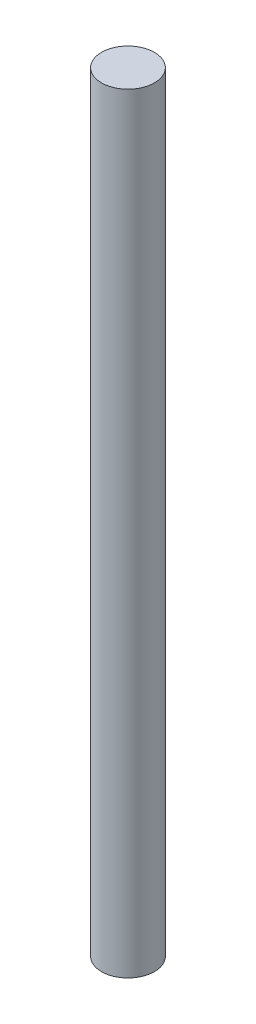
SolidWorks part; units mm, degrees
ref_plane "前视基准面" through (0, 0, 0) normal (0, 0, 1) x (1, 0, 0)
ref_plane "上视基准面" through (0, 0, 0) normal (0, 1, 0) x (1, 0, 0)
ref_plane "右视基准面" through (0, 0, 0) normal (1, 0, 0) x (0, 0, -1)
sketch "草图2" plane through (0, 0, 0) normal (0, 1, 0) x (1, 0, 0)
  circle A0 centre (0, 0) radius 2
extrude "凸台-拉伸1" add sketch "草图2" along normal blind 58.18
